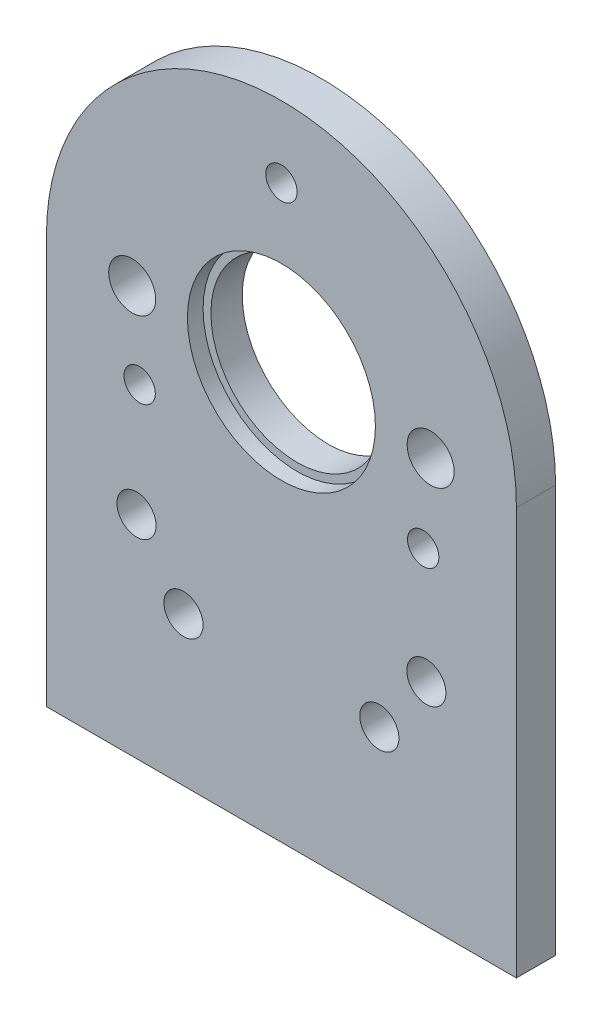
SolidWorks part; units mm, degrees
ref_plane "Front Plane" through (0, 0, 0) normal (0, 0, 1) x (1, 0, 0)
ref_plane "Top Plane" through (0, 0, 0) normal (0, 1, 0) x (1, 0, 0)
ref_plane "Right Plane" through (0, 0, 0) normal (1, 0, 0) x (0, 0, -1)
ref_plane "Plane1" through (0, 0, 3) normal (0, 0, 1) x (1, 0, 0)
sketch "Sketch1" plane through (0, 0, 3) normal (0, 0, 1) x (1, 0, 0)
  line L0 (-15, 0) -> (-15, -26)
  line L1 (-15, -26) -> (15, -26)
  line L2 (15, -26) -> (15, 0)
  arc A0 (15, 0) -> (-15, 0) centre (0, 0) ccw
extrude "Boss-Extrude1" add sketch "Sketch1" against normal blind 2.5
sketch "Sketch2" plane through (0, 0, 0.5) normal (0, 0, -1) x (-1, 0, 0)
  line L0 (-14.25, -25.25) -> (-14.25, 0)
  line L1 (14.25, 0) -> (14.25, -25.25)
  line L2 (14.25, -25.25) -> (-14.25, -25.25)
  arc A0 (-14.25, 0) -> (14.25, 0) centre (0, 0) cw
extrude "Boss-Extrude2" add sketch "Sketch2" along normal blind 0.5
hole_wizard "Ø2.5 (2.5) Diameter Hole1" positions "Sketch4" profile "Sketch3" hole size "Ø2.5" standard "ANSI Metric"
sketch "Sketch4" plane through (0, 0, 0) normal (0, 0, -1) x (-1, 0, 0)
  point P0 (9.25, -12.5)
  point P1 (-9.25, -12.5)
  point P2 (6.25, -16.5)
  point P3 (-6.25, -16.5)
sketch "Sketch3" plane through (-9.25, -12.5, 0) normal (1, 0, 0) x (0, 1, 0)
  line L0 (0, 0) -> (0, 3)
  line L1 (0, 3) -> (1.25, 3)
  line L2 (1.25, 3) -> (1.25, 0)
  line L5 (1.25, 0) -> (0, 0)
  line L11 (0, -6.35) -> (0, 107.95) construction
  dimension "Thru Hole Dia." = 2.5
  dimension "Thru Hole Depth" = 3
hole_wizard "Ø3.0 (3) Diameter Hole1" positions "Sketch6" profile "Sketch5" hole size "Ø3.0" standard "ANSI Metric"
sketch "Sketch6" plane through (0, 0, 0) normal (0, 0, -1) x (-1, 0, 0)
  point P0 (-9.525, 0)
  point P1 (9.525, 0)
sketch "Sketch5" plane through (9.525, 0, 0) normal (1, 0, 0) x (0, 1, 0)
  line L0 (0, 0) -> (0, 3)
  line L1 (0, 3) -> (1.5, 3)
  line L2 (1.5, 3) -> (1.5, 0)
  line L5 (1.5, 0) -> (0, 0)
  line L11 (0, -6.35) -> (0, 107.95) construction
  dimension "Thru Hole Dia." = 3
  dimension "Thru Hole Depth" = 3
hole_wizard "Ø2.0 (2) Diameter Hole1" positions "Sketch8" profile "Sketch7" hole size "Ø2.0" standard "ANSI Metric"
sketch "Sketch8" plane through (0, 0, 0) normal (0, 0, -1) x (-1, 0, 0)
  point P0 (0, 10.45)
  point P1 (9.05, -5.225)
  point P2 (-9.05, -5.225)
sketch "Sketch7" plane through (0, 10.45, 0) normal (1, 0, 0) x (0, 1, 0)
  line L0 (0, 0) -> (0, 3)
  line L1 (0, 3) -> (1, 3)
  line L2 (1, 3) -> (1, 0)
  line L5 (1, 0) -> (0, 0)
  line L11 (0, -6.35) -> (0, 107.95) construction
  dimension "Thru Hole Dia." = 2
  dimension "Thru Hole Depth" = 3
hole_wizard "CBORE for M10 Hex Head Bolt1" positions "Sketch10" profile "Sketch9" counterbore size "M10" standard "ANSI Metric"
sketch "Sketch10" plane through (0, 0, 3) normal (0, 0, 1) x (1, 0, 0)
  point P0 (0, 0)
sketch "Sketch9" plane through (0, 0, 3) normal (1, 0, 0) x (0, -1, 0)
  line L0 (0, 0) -> (0, 3)
  line L1 (0, 3) -> (5.5, 3)
  line L3 (5.5, 3) -> (5.5, 1)
  line L4 (5.5, 1) -> (6, 1)
  line L5 (6, 1) -> (6, 0)
  line L7 (6, 0) -> (0, 0)
  line L11 (0, -6.35) -> (0, 107.95) construction
  dimension "Thru Hole Dia." = 11
  dimension "Thru Hole Depth" = 3
  dimension "C'Bore Dia." = 12
  dimension "C'Bore Depth" = 1
